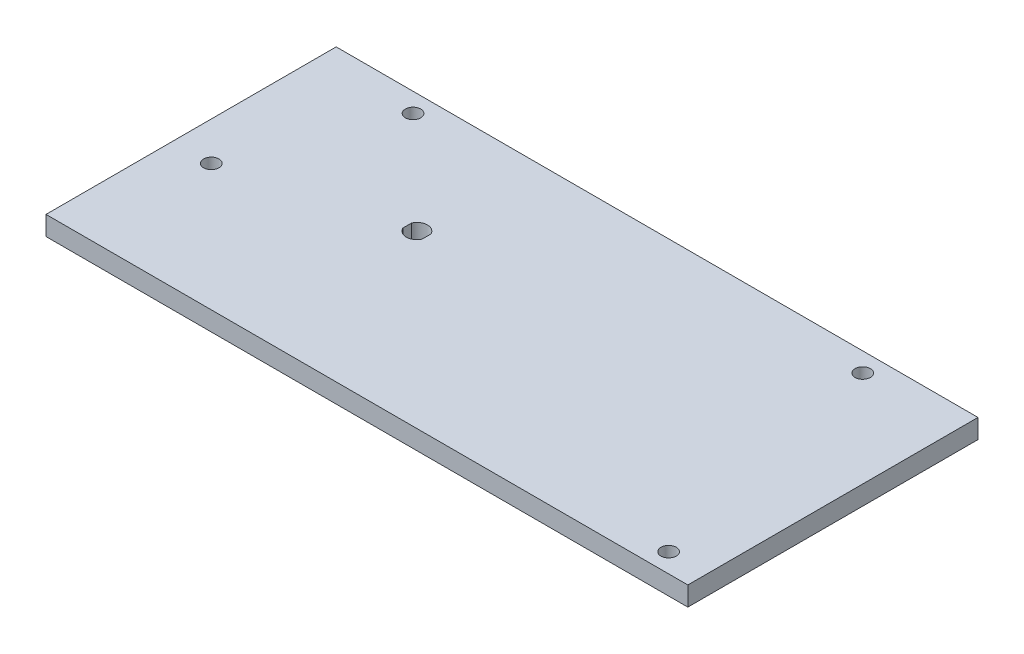
SolidWorks part; units mm, degrees
ref_plane "Front Plane" through (0, 0, 0) normal (0, 0, 1) x (1, 0, 0)
ref_plane "Top Plane" through (0, 0, 0) normal (0, 1, 0) x (1, 0, 0)
ref_plane "Right Plane" through (0, 0, 0) normal (1, 0, 0) x (0, 0, -1)
sketch "Sketch2" plane through (0, 0, 0) normal (0, 1, 0) x (1, 0, 0)
  line L1 (-83.5, -37.75) -> (83.5, -37.75)
  line L2 (-83.5, -37.75) -> (-83.5, 37.75)
  line L3 (-83.5, 37.75) -> (83.5, 37.75)
  line L4 (83.5, -37.75) -> (83.5, 37.75)
  line L5 (-83.5, -37.75) -> (83.5, 37.75) construction
  line L6 (-83.5, 37.75) -> (83.5, -37.75) construction
  circle A0 centre (-58.5, 32.75) radius 2
  circle A1 centre (58.5, 32.75) radius 2
  circle A2 centre (-73.5, -4.75) radius 2
  circle A3 centre (73.5, -32.75) radius 2
  point P0 (0, 0)
  dimension "D3" = 4
  dimension "D4" = 25
  dimension "D6" = 25
  dimension "D7" = 10
  dimension "D8" = 42.5
  dimension "D9" = 5
  dimension "D10" = 10
  dimension "D1" = 167
  dimension "D2" = 75.5
  dimension "D5" = 5
extrude "Boss-Extrude1" add sketch "Sketch2" along normal blind 5
sketch "Sketch3" plane through (0, 5, 0) normal (0, 1, 0) x (1, 0, 0)
  line L0 (-83.5, 37.75) -> (-83.5, -37.75) construction
  line L1 (-78.5, 27.75) -> (-16.5, 27.75) construction
  line L2 (-78.5, 27.75) -> (-78.5, 2.75) construction
  line L3 (-78.5, 2.75) -> (-16.5, 2.75) construction
  line L4 (-16.5, 27.75) -> (-16.5, 2.75) construction
  line L5 (83.5, 37.75) -> (-83.5, 37.75) construction
  line L6 (-34, 7.8956) -> (-34, 5.6044)
  line L7 (-29, 7.8956) -> (-29, 5.6044)
  circle A0 centre (-31.5, 6.75) radius 2.75
  dimension "D5" = 5.5
  dimension "D6" = 4
  dimension "D7" = 15
  dimension "D1" = 25
  dimension "D2" = 62
  dimension "D3" = 5
  dimension "D4" = 10
  dimension "D8" = 5
extrude "Cut-Extrude1" cut sketch "Sketch3" against normal through all contours L7 A0 L6
